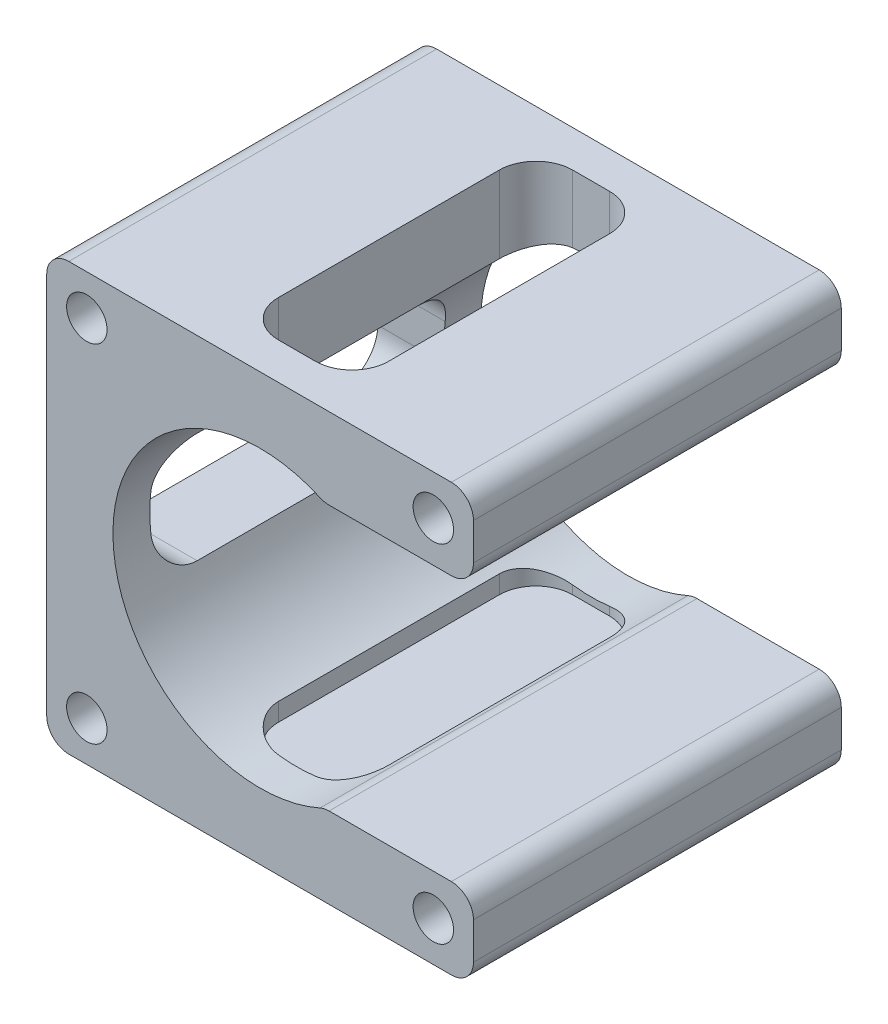
SolidWorks part; units mm, degrees
material "ABS"
ref_plane "Front Plane" through (0, 0, 0) normal (0, 0, 1) x (1, 0, 0)
ref_plane "Top Plane" through (0, 0, 0) normal (0, 1, 0) x (1, 0, 0)
ref_plane "Right Plane" through (0, 0, 0) normal (1, 0, 0) x (0, 0, -1)
sketch "Sketch1" plane through (0, 0, 0) normal (0, 0, 1) x (1, 0, 0)
  line L0 (-23.55, 23.55) -> (23.55, 23.55) construction
  line L1 (26, -29) -> (-26, -29)
  line L2 (29, -26) -> (29, -21)
  line L3 (26, 29) -> (-26, 29)
  line L4 (-29, -26) -> (-29, 26)
  line L5 (29, -29) -> (-29, 29) construction
  line L6 (29, 29) -> (-29, -29) construction
  line L7 (-23.55, 23.55) -> (-23.55, -23.55) construction
  line L8 (23.55, 23.55) -> (23.55, -23.55) construction
  line L9 (9.3808, 18) -> (26, 18)
  line L10 (9.3808, -18) -> (26, -18)
  line L11 (29, 21) -> (29, 26)
  arc A0 (8.1572, 18.2609) -> (8.1572, -18.2609) centre (0, 0) ccw
  circle A1 centre (-23.55, 23.55) radius 2.75
  circle A2 centre (-23.55, -23.55) radius 2.75
  circle A3 centre (23.55, -23.55) radius 2.75
  circle A4 centre (23.55, 23.55) radius 2.75
  arc A5 (26, -18) -> (29, -21) centre (26, -21) cw
  arc A6 (9.3808, -18) -> (8.1572, -18.2609) centre (9.3808, -21) ccw
  arc A7 (9.3808, 18) -> (8.1572, 18.2609) centre (9.3808, 21) cw
  arc A8 (29, 21) -> (26, 18) centre (26, 21) cw
  arc A9 (29, 26) -> (26, 29) centre (26, 26) ccw
  arc A10 (26, -29) -> (29, -26) centre (26, -26) ccw
  arc A11 (-26, -29) -> (-29, -26) centre (-26, -26) cw
  arc A12 (-26, 29) -> (-29, 26) centre (-26, 26) ccw
  dimension "D1" = 40
  dimension "D4" = 5.5
  dimension "D5" = 5.5
  dimension "D6" = 5.5
  dimension "D7" = 5.5
  dimension "D11" = 3
  dimension "D2" = 58
  dimension "D3" = 58
  dimension "D8" = 47.1
  dimension "D9" = 36
  dimension "D10" = 18
extrude "Boss-Extrude1" add sketch "Sketch1" along normal blind 50
sketch "Sketch2" plane through (0, 29, 0) normal (0, 1, 0) x (1, 0, 0)
  line L0 (0, 0) -> (0, -25) construction
  line L1 (-2.51, -45) -> (2.51, -45)
  line L2 (-7.5, -40.01) -> (-7.5, -9.99)
  line L3 (-2.51, -5) -> (2.51, -5)
  line L4 (7.5, -40.01) -> (7.5, -9.99)
  line L5 (-7.5, -45) -> (7.5, -5) construction
  line L6 (-7.5, -5) -> (7.5, -45) construction
  arc A0 (2.51, -45) -> (7.5, -40.01) centre (2.51, -40.01) ccw
  arc A1 (-2.51, -45) -> (-7.5, -40.01) centre (-2.51, -40.01) cw
  arc A2 (2.51, -5) -> (7.5, -9.99) centre (2.51, -9.99) cw
  arc A3 (-7.5, -9.99) -> (-2.51, -5) centre (-2.51, -9.99) cw
  point P0 (0, -25)
  dimension "D4" = 4.99
  dimension "D1" = 25
  dimension "D2" = 40
  dimension "D3" = 15
extrude "Cut-Extrude1" cut sketch "Sketch2" against normal blind 50
sketch "Sketch3" plane through (-29, 0, 0) normal (-1, 0, 0) x (0, 0, 1)
  line L0 (0, 0) -> (25, 0) construction
  line L1 (9.99, -7.5) -> (40.01, -7.5)
  line L2 (5, -2.51) -> (5, 2.51)
  line L3 (9.99, 7.5) -> (40.01, 7.5)
  line L4 (45, -2.51) -> (45, 2.51)
  line L5 (5, -7.5) -> (45, 7.5) construction
  line L6 (5, 7.5) -> (45, -7.5) construction
  arc A0 (40.01, 7.5) -> (45, 2.51) centre (40.01, 2.51) cw
  arc A1 (40.01, -7.5) -> (45, -2.51) centre (40.01, -2.51) ccw
  arc A2 (9.99, -7.5) -> (5, -2.51) centre (9.99, -2.51) cw
  arc A3 (5, 2.51) -> (9.99, 7.5) centre (9.99, 2.51) cw
  point P0 (25, 0)
  dimension "D4" = 4.99
  dimension "D1" = 25
  dimension "D2" = 40
  dimension "D3" = 15
extrude "Cut-Extrude2" cut sketch "Sketch3" against normal blind 50
